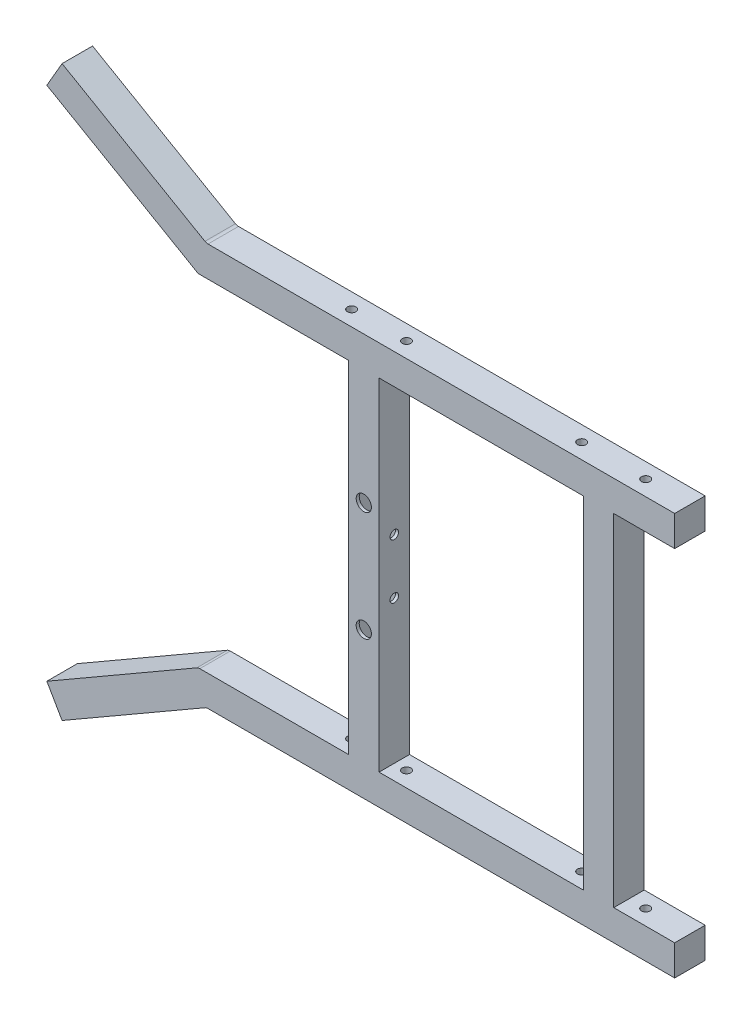
SolidWorks part; units mm, degrees
ref_plane "Front Plane" through (0, 0, 0) normal (0, 0, 1) x (1, 0, 0)
ref_plane "Top Plane" through (0, 0, 0) normal (0, 1, 0) x (1, 0, 0)
ref_plane "Right Plane" through (0, 0, 0) normal (1, 0, 0) x (0, 0, -1)
sketch "Sketch1" plane through (0, 0, 0) normal (0, 0, 1) x (1, 0, 0)
  line L0 (-4036.9333, 0) -> (197809.7327, 0) construction
  line L1 (0, -4036.9333) -> (0, 197809.7327) construction
  line L2 (-242.4871, -140) -> (0, 0)
  line L3 (0, 0) -> (775, 0)
  line L4 (265, 0) -> (265, 305)
  line L5 (-735, 305) -> (49265, 305) construction
  line L6 (650, 0) -> (650, 305)
  line L7 (-229.9871, -161.6506) -> (6.6987, -25)
  line L8 (6.6987, -25) -> (775, -25)
  line L9 (-254.9871, -118.3494) -> (-6.6987, 25)
  line L10 (-6.6987, 25) -> (775, 25)
  line L11 (-254.9871, -118.3494) -> (-229.9871, -161.6506)
  line L12 (775, 25) -> (775, -25)
  point P7 (265, 0)
  point P11 (650, 0)
  dimension "D1" = 775
  dimension "D2" = 150
  dimension "D3" = 265
  dimension "D4" = 305
  dimension "D5" = 385
  dimension "D6" = 280
  dimension "D7" = 25
  dimension "D8" = 25
extrude "Boss-Extrude4" add sketch "Sketch1" along normal mid plane 50 contours L9 L11 L2 L3 L4 L10 | L12 L3 L2 L11 L7 L8 | L10 L4 L3 L6 | L12 L10 L6 L3
fillet "Fillet1" radius 10 1 edges at (-6.6987, 25, 0)
fillet "Fillet2" radius 10 1 edges at (6.6987, -25, 0)
ref_plane "Plane5" through (0, 25, 0) normal (0, 1, 0) x (1, 0, 0)
sketch "Sketch8" plane through (0, 25, 0) normal (0, 1, 0) x (1, 0, 0)
  line L0 (-4.0192, 25) -> (775, 25) construction
  line L1 (290, -25) -> (240, -25)
  line L2 (290, -25) -> (290, 25)
  line L3 (290, 25) -> (240, 25)
  line L4 (240, -25) -> (240, 25)
  line L5 (290, -25) -> (240, 25) construction
  line L6 (290, 25) -> (240, -25) construction
  line L7 (285, 20) -> (245, 20)
  line L8 (625.0336, -25) -> (675.0336, -25)
  line L9 (625.0336, -25) -> (625.0336, 25)
  line L10 (625.0336, 25) -> (675.0336, 25)
  line L11 (675.0336, -25) -> (675.0336, 25)
  line L12 (625.0336, -25) -> (675.0336, 25) construction
  line L13 (625.0336, 25) -> (675.0336, -25) construction
  line L14 (245, -20) -> (245, 20)
  line L15 (285, -20) -> (245, -20)
  line L16 (285, -20) -> (285, 20)
  line L17 (630.0336, 20) -> (670.0336, 20)
  line L18 (670.0336, -20) -> (670.0336, 20)
  line L19 (630.0336, -20) -> (670.0336, -20)
  line L20 (630.0336, -20) -> (630.0336, 20)
  point P0 (265, 0)
  point P8 (650.0336, 0)
  point P9 (650.0336, 0)
  dimension "D1" = 50
  dimension "D2" = 50
  dimension "D3" = 50
extrude "Boss-Extrude5" add sketch "Sketch8" along normal up to vertex (280 mm away) up to point (265, 305, 0)
sketch "Sketch9" plane through (0, 0, 0) normal (0, 0, 1) x (1, 0, 0)
  line L0 (265, 0) -> (310, 0)
  line L1 (0, 0) -> (775, 0) construction
  line L2 (290, 25) -> (625.0336, 25)
  line L3 (457.5168, -975) -> (457.5168, 49025) construction
  circle A0 centre (310, 0) radius 7
  circle A1 centre (605.0336, 0) radius 7
  point P13 (457.5168, 25)
  dimension "D2" = 14
  dimension "D1" = 45
sketch "Sketch11" plane through (290, 0, 0) normal (1, 0, 0) x (0, 0, -1)
  line L0 (0, 0) -> (0, 305) construction
  line L1 (0, 24.3927) -> (0, 305)
  circle A0 centre (0, 260) radius 7
  circle A1 centre (1.113, 253.0891) radius 2.3116
  point P6 (0, 260)
  dimension "D2" = 14
  dimension "D1" = 45
extrude "Cut-Extrude2" cut sketch "Sketch11" along normal blind 51 and the other way through all contours A0
mirror "Mirror1" about plane through (0, 305, 0) normal (0, -1, 0) of bodies 110
sketch "Sketch12" plane through (0, -25, 0) normal (0, -1, 0) x (1, 0, 0)
  line L0 (702.5, 0) -> (597.5, 0) construction
  line L1 (6.6987, 0) -> (775, 0) construction
  circle A0 centre (310, 0) radius 7
  circle A1 centre (220, 0) radius 7
  circle A2 centre (597.5, 0) radius 7
  circle A3 centre (702.5, 0) radius 7
  point P0 (265, 0)
  point P6 (310, 0)
  point P8 (650, 0)
  point P16 (650, 0)
  dimension "D1" = 14
  dimension "D3" = 14
  dimension "D4" = 14
  dimension "D2" = 45
extrude "Cut-Extrude3" cut sketch "Sketch12" against normal through all
sketch "Sketch13" plane through (0, 0, 25) normal (0, 0, 1) x (1, 0, 0)
  line L0 (265, 215) -> (265, 395) construction
  line L1 (240, 305) -> (286.9084, 305)
  line L2 (240, 585) -> (240, 25) construction
  line L3 (-200735, 305) -> (249265, 305) construction
  circle A0 centre (265, 395) radius 12.5
  circle A1 centre (265, 215) radius 12.5
  point P0 (265, 305)
  point P6 (265, 305)
  dimension "D1" = 25
  dimension "D2" = 180
extrude "Cut-Extrude4" cut sketch "Sketch13" against normal blind 25 contours A0 | A1
